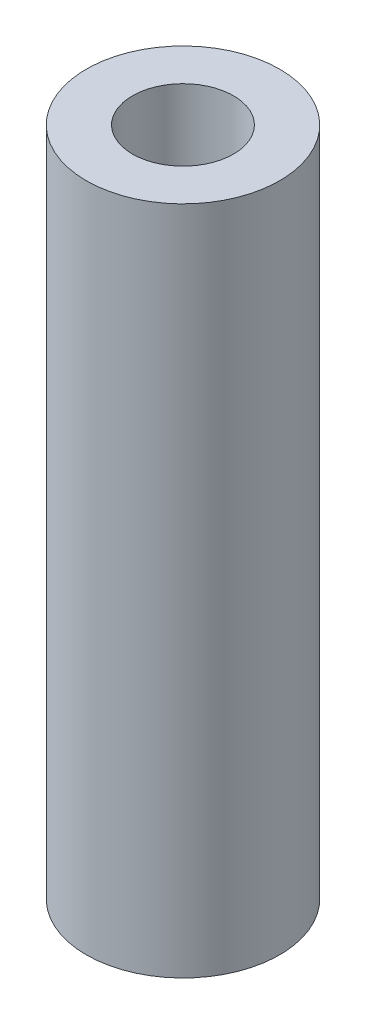
SolidWorks part; units mm, degrees
ref_plane "Front Plane" through (0, 0, 0) normal (0, 0, 1) x (1, 0, 0)
ref_plane "Top Plane" through (0, 0, 0) normal (0, 1, 0) x (1, 0, 0)
ref_plane "Right Plane" through (0, 0, 0) normal (1, 0, 0) x (0, 0, -1)
sketch "Sketch1" plane through (0, 0, 0) normal (0, 1, 0) x (1, 0, 0)
  circle A0 centre (0, 0) radius 2.4892
  circle A1 centre (0, 0) radius 4.7625
  dimension "D1" = 4.9784
  dimension "D2" = 9.525
extrude "Boss-Extrude1" add sketch "Sketch1" along normal blind 33.02
